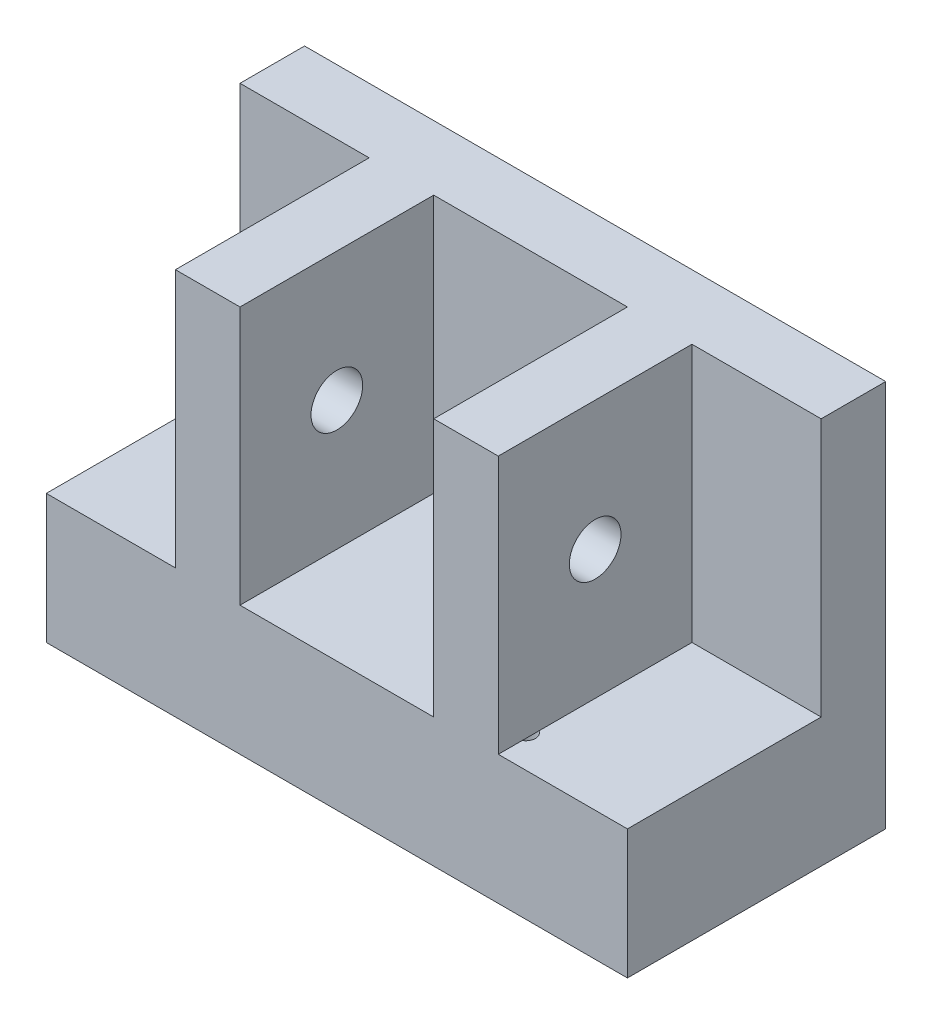
SolidWorks part; units mm, degrees
ref_plane "Front Plane" through (0, 0, 0) normal (0, 0, 1) x (1, 0, 0)
ref_plane "Top Plane" through (0, 0, 0) normal (0, 1, 0) x (1, 0, 0)
ref_plane "Right Plane" through (0, 0, 0) normal (1, 0, 0) x (0, 0, -1)
sketch "Sketch3" plane through (0, 0, 0) normal (0, 1, 0) x (1, 0, 0)
  line L0 (-25, 0) -> (-15, 0)
  line L1 (-15, 0) -> (-15, 30)
  line L2 (-15, 30) -> (15, 30)
  line L3 (15, 30) -> (15, 0)
  line L4 (15, 0) -> (25, 0)
  line L5 (25, 0) -> (25, 40)
  line L6 (25, 40) -> (-25, 40)
  line L7 (-25, 40) -> (-25, 0)
  line L8 (25, 30) -> (45, 30)
  line L9 (45, 30) -> (45, 40)
  line L10 (45, 40) -> (25, 40)
  line L11 (0, 40) -> (0, 30) construction
  line L12 (-45, 40) -> (-25, 40)
  line L13 (-45, 30) -> (-45, 40)
  line L14 (-25, 30) -> (-45, 30)
  point P8 (0, 30)
  dimension "D1" = 40
  dimension "D2" = 10
  dimension "D3" = 30
  dimension "D4" = 10
  dimension "D5" = 20
extrude "Boss-Extrude1" add sketch "Sketch3" along normal blind 40 contours L14 L7 L12 L13 | L11 L6 L7 L0 L1 L2 | L6 L11 L2 L3 L4 L5 | L9 L10 L5 L8
sketch "Sketch4" plane through (-15, 0, 0) normal (1, 0, 0) x (0, 0, -1)
  line L1 (0, 40) -> (0, 0) construction
  line L2 (0, 0) -> (30, 0) construction
  circle A0 centre (15, 20) radius 4
  point P9 (0, 20)
  point P11 (15, 0)
  dimension "D1" = 8
extrude "Cut-Extrude1" cut sketch "Sketch4" against normal through all both and the other way through all
sketch "Sketch7" plane through (0, 0, 0) normal (0, -1, 0) x (1, 0, 0)
  line L0 (45, -30) -> (45, -40) construction
  line L1 (-45, -40) -> (45, -40)
  line L2 (-45, -40) -> (-45, 0)
  line L3 (-45, 0) -> (45, 0)
  line L4 (45, -40) -> (45, 0)
  line L5 (15, 0) -> (25, 0) construction
extrude "Boss-Extrude3" add sketch "Sketch7" along normal blind 20
sketch "Sketch8" plane through (0, -20, 0) normal (0, -1, 0) x (1, 0, 0)
  line L0 (0, 0) -> (0, -40) construction
  line L1 (45, 0) -> (-45, 0) construction
  line L2 (-45, -40) -> (45, -40) construction
  circle A0 centre (-24.25, -5) radius 1.5
  circle A1 centre (24.25, -5) radius 1.5
  dimension "D1" = 3
  dimension "D2" = 48.5
  dimension "D3" = 35
extrude "Cut-Extrude3" cut sketch "Sketch8" against normal blind 20
equation "\"D4@Sketch3\"=\"D2@Sketch3\""
